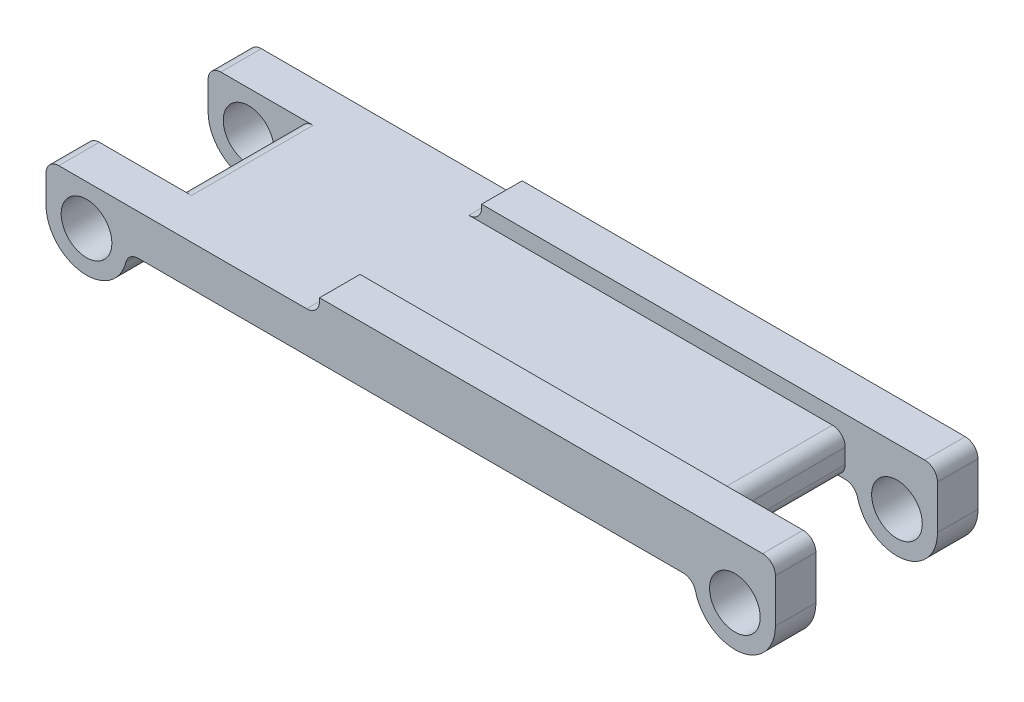
SolidWorks part; units mm, degrees
ref_plane "Front Plane" through (0, 0, 0) normal (0, 0, 1) x (1, 0, 0)
ref_plane "Top Plane" through (0, 0, 0) normal (0, 1, 0) x (1, 0, 0)
ref_plane "Right Plane" through (0, 0, 0) normal (1, 0, 0) x (0, 0, -1)
sketch "Sketch1" plane through (0, 0, 0) normal (0, 0, 1) x (1, 0, 0)
  line L0 (105.95, 8.85) -> (36.5125, 8.85)
  line L1 (-6.35, 4.35) -> (-6.35, 0)
  line L2 (107.95, 6.85) -> (107.95, 0)
  line L3 (0, 0) -> (101.6, 0) construction
  line L5 (-4.35, 6.35) -> (34.5125, 6.35)
  line L6 (50.8, 12.979) -> (50.8, -9.4606) construction
  line L8 (8.1069, 0) -> (93.4931, 0)
  line L9 (36.5125, 8.85) -> (36.5125, 8.35)
  circle A0 centre (0, 0) radius 3.9688
  circle A1 centre (0, 0) radius 6.35 construction
  circle A2 centre (101.6, 0) radius 3.9687
  circle A3 centre (101.6, 0) radius 6.35 construction
  arc A4 (-6.35, 4.35) -> (-4.35, 6.35) centre (-4.35, 4.35) cw
  arc A5 (107.95, 0) -> (101.6, -6.35) centre (101.6, 0) cw
  arc A6 (107.95, 6.85) -> (105.95, 8.85) centre (105.95, 6.85) ccw
  arc A7 (-6.35, 0) -> (0, -6.35) centre (0, 0) ccw
  arc A8 (6.1652, -1.521) -> (0, -6.35) centre (0, 0) cw
  arc A9 (8.1069, 0) -> (6.1652, -1.521) centre (8.1069, -2) ccw
  arc A10 (93.4931, 0) -> (95.4348, -1.521) centre (93.4931, -2) cw
  arc A11 (95.4348, -1.521) -> (101.6, -6.35) centre (101.6, 0) ccw
  circle A12 centre (50.8, 6.35) radius 2.5 construction
  arc A13 (34.5125, 6.35) -> (36.5125, 8.35) centre (34.5125, 8.35) ccw
  point P25 (6.35, 0)
  dimension "D1" = 7.9375
  dimension "D2" = 2
  dimension "D3" = 2
  dimension "D4" = 2
  dimension "D5" = 2
extrude "Boss-Extrude1" add sketch "Sketch1" along normal blind 6.35
ref_plane "Plane1" through (0, 0, 6.35) normal (0, 0, 1) x (1, 0, 0)
sketch "Sketch3" plane through (0, 0, 6.35) normal (0, 0, 1) x (1, 0, 0)
  line L0 (91.4931, 6.35) -> (10.1069, 6.35)
  line L1 (8.1069, 2) -> (8.1069, 4.35)
  line L2 (93.4931, 2) -> (93.4931, 4.35)
  line L3 (0, 0) -> (101.6, 0) construction
  line L6 (50.8, 12.979) -> (50.8, -9.4606) construction
  line L8 (10.1069, 0) -> (91.4931, 0)
  arc A0 (8.1069, 4.35) -> (10.1069, 6.35) centre (10.1069, 4.35) cw
  circle A1 centre (0, 0) radius 6.35 construction
  circle A3 centre (101.6, 0) radius 6.35 construction
  arc A4 (10.1069, 0) -> (8.1069, 2) centre (10.1069, 2) cw
  arc A5 (93.4931, 2) -> (91.4931, 0) centre (91.4931, 2) cw
  arc A6 (93.4931, 4.35) -> (91.4931, 6.35) centre (91.4931, 4.35) ccw
  point P13 (8.1069, 0)
  point P16 (93.4931, 0)
  point P25 (6.35, 0)
  dimension "D1" = 2
  dimension "D2" = 2
extrude "Boss-Extrude2" add sketch "Sketch3" along normal blind 19.05
ref_plane "Plane2" through (0, 0, 25.4) normal (0, 0, 1) x (1, 0, 0)
sketch "Sketch4" plane through (0, 0, 25.4) normal (0, 0, 1) x (1, 0, 0)
  line L0 (-4.35, 6.35) -> (34.5125, 6.35)
  line L1 (-6.35, 4.35) -> (-6.35, 0)
  line L2 (107.95, 6.85) -> (107.95, 0)
  line L3 (0, 0) -> (101.6, 0) construction
  line L4 (-6.35, 12.979) -> (50.8, 12.979) construction
  line L6 (50.8, 12.979) -> (50.8, -9.4606) construction
  line L7 (36.5125, 8.85) -> (105.95, 8.85)
  line L8 (8.1069, 0) -> (93.4931, 0)
  line L10 (36.5125, 8.85) -> (36.5125, 8.35)
  circle A0 centre (0, 0) radius 3.9688
  circle A1 centre (0, 0) radius 6.35 construction
  circle A2 centre (101.6, 0) radius 3.9687
  circle A3 centre (101.6, 0) radius 6.35 construction
  arc A4 (-6.35, 4.35) -> (-4.35, 6.35) centre (-4.35, 4.35) cw
  arc A5 (107.95, 0) -> (101.6, -6.35) centre (101.6, 0) cw
  arc A6 (34.5125, 6.35) -> (36.5125, 8.35) centre (34.5125, 8.35) ccw
  arc A7 (-6.35, 0) -> (0, -6.35) centre (0, 0) ccw
  arc A8 (6.1652, -1.521) -> (0, -6.35) centre (0, 0) cw
  arc A9 (8.1069, 0) -> (6.1652, -1.521) centre (8.1069, -2) ccw
  arc A10 (93.4931, 0) -> (95.4348, -1.521) centre (93.4931, -2) cw
  arc A11 (95.4348, -1.521) -> (101.6, -6.35) centre (101.6, 0) ccw
  circle A12 centre (50.8, 6.35) radius 2.5 construction
  arc A13 (107.95, 6.85) -> (105.95, 8.85) centre (105.95, 6.85) ccw
  point P25 (6.35, 0)
  dimension "D1" = 7.9375
  dimension "D2" = 2
  dimension "D3" = 5
  dimension "D4" = 2
  dimension "D5" = 2
  dimension "D6" = 2
extrude "Boss-Extrude3" add sketch "Sketch4" along normal blind 6.35
